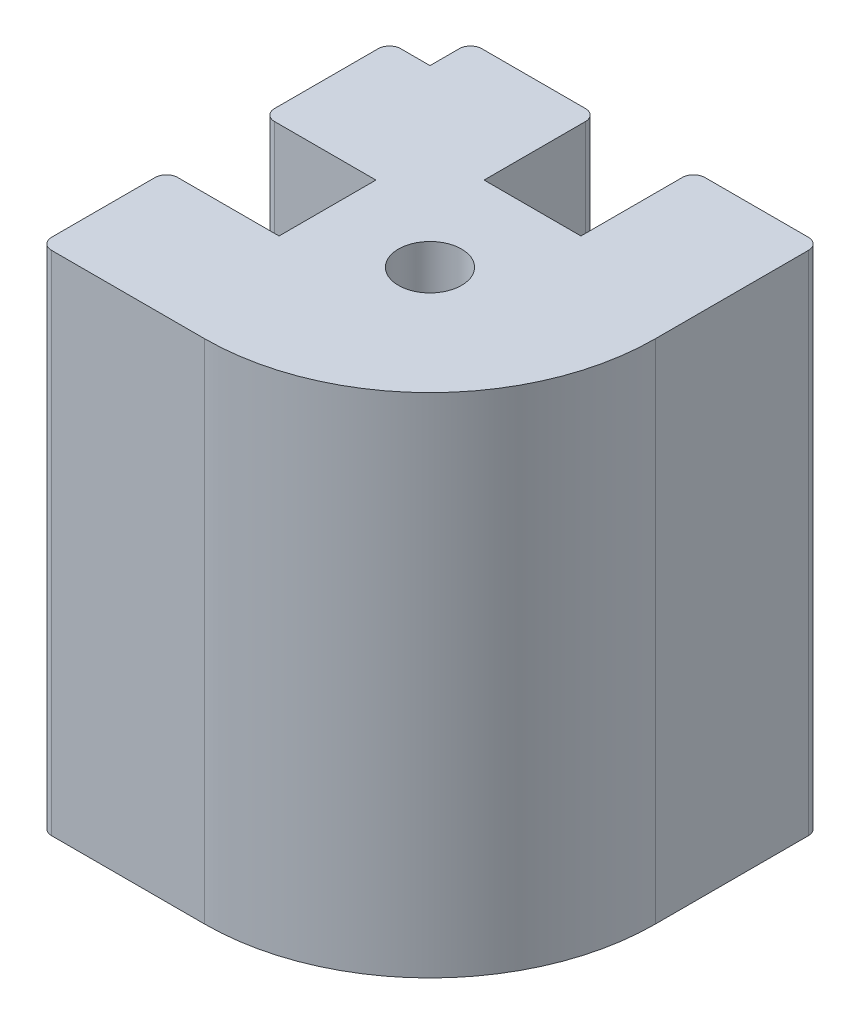
SolidWorks part; units mm, degrees
ref_plane "Front Plane" through (0, 0, 0) normal (0, 0, 1) x (1, 0, 0)
ref_plane "Top Plane" through (0, 0, 0) normal (0, 1, 0) x (1, 0, 0)
ref_plane "Right Plane" through (0, 0, 0) normal (1, 0, 0) x (0, 0, -1)
sketch "Sketch1" plane through (0, 0, 0) normal (0, 1, 0) x (1, 0, 0)
  line L0 (-19.0992, -15.5) -> (-19.0992, -4.3)
  line L1 (-19.0992, -4.3) -> (-9.0992, -4.3)
  line L2 (-9.0992, -4.3) -> (-9.0992, 4.3)
  line L3 (-9.0992, 4.3) -> (-19.0992, 4.3)
  line L4 (-19.0992, 4.3) -> (-19.0992, 15.5)
  line L5 (-19.0992, 15.5) -> (-15.5, 15.5)
  line L6 (-15.5, 15.5) -> (-15.5, 19.0992)
  line L7 (-15.5, 19.0992) -> (-4.3, 19.0992)
  line L8 (-4.3, 19.0992) -> (-4.3, 9.0992)
  line L9 (-4.3, 9.0992) -> (4.3, 9.0992)
  line L10 (4.3, 9.0992) -> (4.3, 19.0992)
  line L11 (4.3, 19.0992) -> (15.5, 19.0992)
  line L12 (15.5, 19.0992) -> (15.5, -15.5)
  line L13 (15.5, -15.5) -> (-19.0992, -15.5)
  circle A0 centre (0, 0) radius 2.8
  point P5 (-9.0992, 0)
  point P15 (0, 9.0992)
  dimension "D4" = 5.6
  dimension "D1" = 8.6
  dimension "D2" = 10
  dimension "D3" = 31
extrude "Boss-Extrude1" add sketch "Sketch1" along normal blind 45
fillet "Fillet1" radius 1 8 edges at (15.5, 22.5, -19.0992) (4.3, 22.5, -19.0992) (-4.3, 22.5, -19.0992) (-15.5, 22.5, -19.0992) (-19.0992, 22.5, -15.5) (-19.0992, 22.5, 4.3) (-19.0992, 22.5, -4.3) (-19.0992, 22.5, 15.5)
fillet "Fillet2" radius 20 1 edges at (15.5, 22.5, 15.5)
